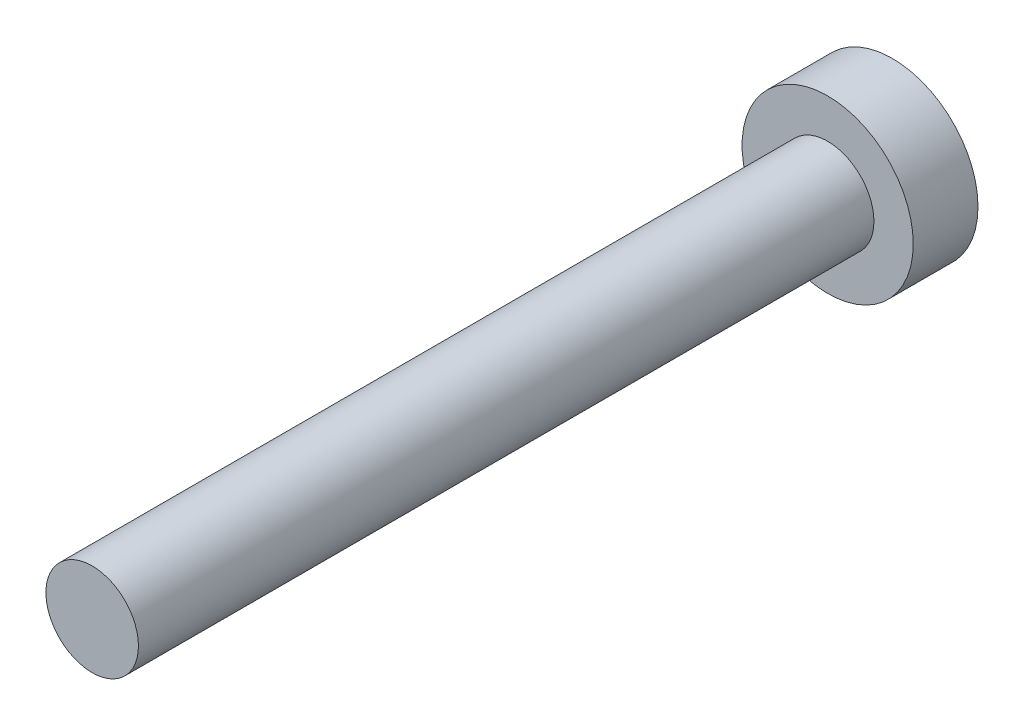
SolidWorks part; units mm, degrees
ref_plane "Спереди" through (0, 0, 0) normal (0, 0, 1) x (1, 0, 0)
ref_plane "Сверху" through (0, 0, 0) normal (0, 1, 0) x (1, 0, 0)
ref_plane "Справа" through (0, 0, 0) normal (1, 0, 0) x (0, 0, -1)
sketch "Эскиз1" plane through (0, 0, 0) normal (0, 0, 1) x (1, 0, 0)
  circle A0 centre (0, 0) radius 1.85
  dimension "D1" = 3.7
extrude "Бобышка-Вытянуть1" add sketch "Эскиз1" along normal blind 1.4
sketch "Эскиз2" plane through (0, 0, 1.4) normal (0, 0, 1) x (1, 0, 0)
  circle A0 centre (0, 0) radius 1
  dimension "D1" = 2
extrude "Бобышка-Вытянуть2" add sketch "Эскиз2" along normal offset from surface (15.9 mm away) 17.3 up to face at (1.85, 0, 0)
